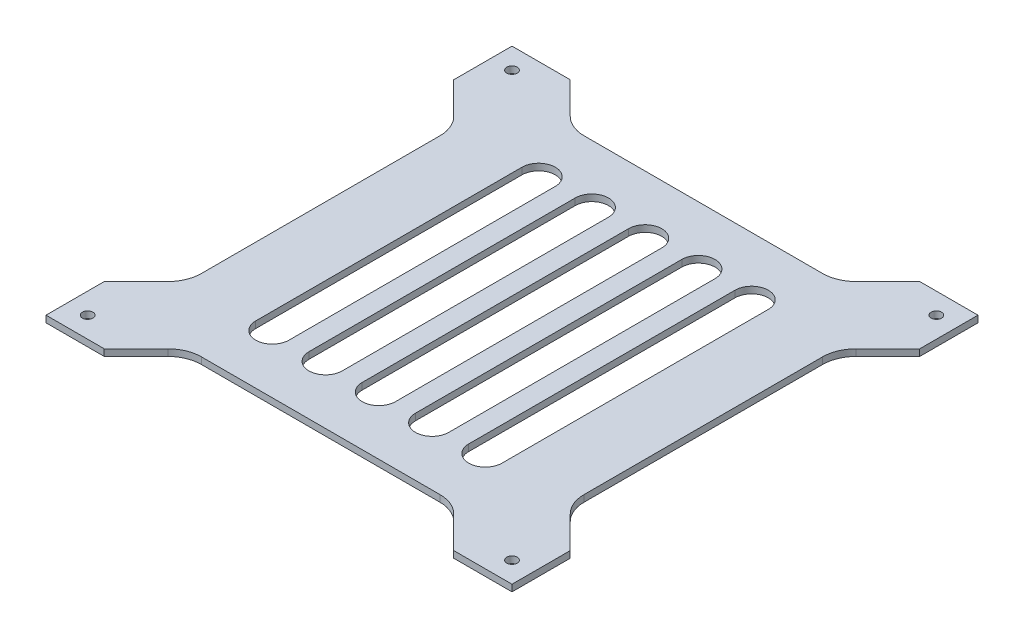
SolidWorks part; units mm, degrees
ref_plane "前视基准面" through (0, 0, 0) normal (0, 0, 1) x (1, 0, 0)
ref_plane "上视基准面" through (0, 0, 0) normal (0, 1, 0) x (1, 0, 0)
ref_plane "右视基准面" through (0, 0, 0) normal (1, 0, 0) x (0, 0, -1)
sketch "草图1" plane through (0, 0, 0) normal (0, 1, 0) x (1, 0, 0)
  line L0 (-52.5, 70) -> (-40, 57.5)
  line L1 (-70, -70) -> (-52.5, -70)
  line L2 (-70, -70) -> (-70, -52.5)
  line L3 (-70, 70) -> (-52.5, 70)
  line L4 (70, -70) -> (70, -52.5)
  line L5 (-70, -70) -> (70, 70) construction
  line L6 (-70, 70) -> (70, -70) construction
  line L7 (-40, 57.5) -> (40, 57.5)
  line L8 (0, 57.5) -> (0, 0) construction
  line L9 (52.5, 70) -> (40, 57.5)
  line L10 (-70, 0) -> (70, 0) construction
  line L11 (-52.5, -70) -> (-40, -57.5)
  line L12 (-40, -57.5) -> (40, -57.5)
  line L13 (52.5, -70) -> (40, -57.5)
  line L14 (70, -52.5) -> (57.5, -40)
  line L15 (57.5, 40) -> (57.5, -40)
  line L16 (70, 52.5) -> (57.5, 40)
  line L17 (-70, -52.5) -> (-57.5, -40)
  line L18 (-57.5, 40) -> (-57.5, -40)
  line L19 (-70, 52.5) -> (-57.5, 40)
  line L20 (52.5, 70) -> (70, 70)
  line L21 (-70, 52.5) -> (-70, 70)
  line L22 (70, 52.5) -> (70, 70)
  line L23 (52.5, -70) -> (70, -70)
  circle A0 centre (-63.7413, 63.7413) radius 1.569
  circle A1 centre (63.7413, 63.7413) radius 1.569
  circle A2 centre (63.7413, -63.7413) radius 1.569
  circle A3 centre (-63.7413, -63.7413) radius 1.569
  point P8 (0, 0)
  point P26 (-156.5728, -4.8437)
  point P37 (0, 0)
  dimension "D1" = 140
  dimension "D2" = 140
  dimension "D3" = 12.5
  dimension "D4" = 40
  dimension "D5" = 135
  dimension "D6" = 2
extrude "凸台-拉伸1" add sketch "草图1" along normal blind 2
fillet "圆角1" radius 10 8 edges at (57.5, 1, 40) (-57.5, 1, -40) (-57.5, 1, 40) (-40, 1, 57.5) (40, 1, 57.5) (57.5, 1, -40) (40, 1, -57.5) (-40, 1, -57.5)
sketch "草图2" plane through (0, 2, 0) normal (0, 1, 0) x (1, 0, 0)
  line L0 (0, -40) -> (0, 40) construction
  line L1 (-5, -40) -> (-5, 40)
  line L2 (5, -40) -> (5, 40)
  line L3 (16, -40) -> (16, 40) construction
  line L4 (11, -40) -> (11, 40)
  line L5 (21, -40) -> (21, 40)
  line L6 (32, -40) -> (32, 40) construction
  line L7 (27, -40) -> (27, 40)
  line L8 (37, -40) -> (37, 40)
  line L9 (-16, -40) -> (-16, 40) construction
  line L10 (-21, -40) -> (-21, 40)
  line L11 (-11, -40) -> (-11, 40)
  line L12 (-32, -40) -> (-32, 40) construction
  line L13 (-37, -40) -> (-37, 40)
  line L14 (-27, -40) -> (-27, 40)
  arc A0 (-5, -40) -> (5, -40) centre (0, -40) ccw
  arc A1 (5, 40) -> (-5, 40) centre (0, 40) ccw
  arc A2 (11, -40) -> (21, -40) centre (16, -40) ccw
  arc A3 (21, 40) -> (11, 40) centre (16, 40) ccw
  arc A4 (27, -40) -> (37, -40) centre (32, -40) ccw
  arc A5 (37, 40) -> (27, 40) centre (32, 40) ccw
  arc A6 (-21, -40) -> (-11, -40) centre (-16, -40) ccw
  arc A7 (-11, 40) -> (-21, 40) centre (-16, 40) ccw
  arc A8 (-37, -40) -> (-27, -40) centre (-32, -40) ccw
  arc A9 (-27, 40) -> (-37, 40) centre (-32, 40) ccw
  point P2 (0, 0)
  point P11 (16, 0)
  point P18 (32, 0)
  point P25 (-16, 0)
  point P32 (-32, 0)
  dimension "D2" = 5
  dimension "D1" = 80
  dimension "D3" = 3
  dimension "D4" = 3
extrude "切除-拉伸1" cut sketch "草图2" against normal blind 2
